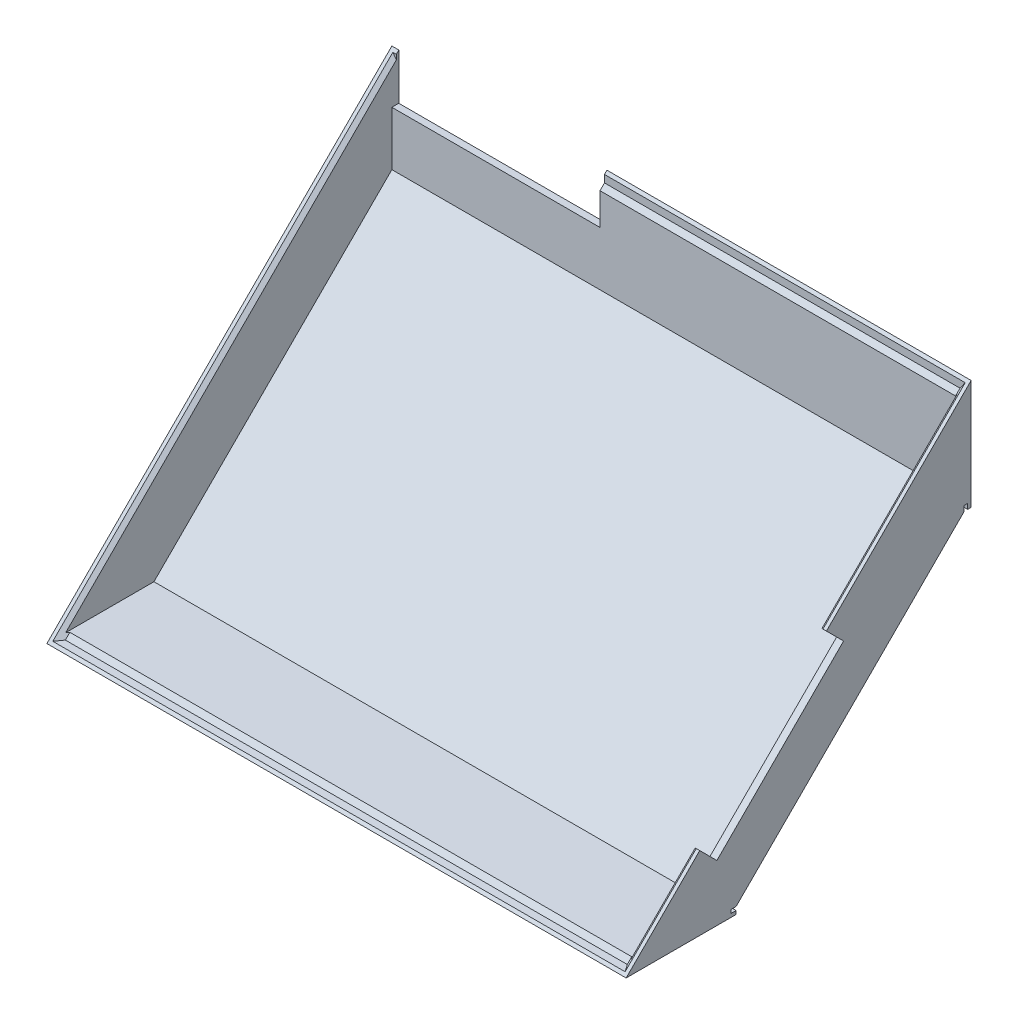
SolidWorks part; units mm, degrees
ref_plane "Front Plane" through (0, 0, 0) normal (0, 0, 1) x (1, 0, 0)
ref_plane "Top Plane" through (0, 0, 0) normal (0, 1, 0) x (1, 0, 0)
ref_plane "Right Plane" through (0, 0, 0) normal (1, 0, 0) x (0, 0, -1)
sketch "Sketch1" plane through (0, 0, 0) normal (1, 0, 0) x (0, 0, -1)
  line L0 (0, 0) -> (31.6985, 0)
  line L1 (99.4594, 67.7609) -> (99.4594, 99.4594)
  line L2 (99.4594, 99.4594) -> (0, 0)
  line L6 (31.6985, 2) -> (31.6985, 0)
  line L7 (97.4594, 67.7609) -> (99.4594, 67.7609)
  line L9 (97.4594, 67.7609) -> (31.6985, 2)
  dimension "D1" = 93
  dimension "D2" = 2
  dimension "D3" = 2
  dimension "D4" = 21
  dimension "D5" = 45
extrude "Boss-Extrude2" add sketch "Sketch1" along normal blind 167 contours L2 L0 L6 L9 L7 L1
sketch "Sketch5" plane through (167, 0, 0) normal (1, 0, 0) x (0, 0, -1)
  line L0 (99.4594, 99.4594) -> (0, 0) construction
  line L1 (97.4594, 97.4594) -> (2, 2)
  line L27 (29.6985, 2) -> (29.6985, 2.8284)
  line L28 (4.8284, 2) -> (29.6985, 2)
  line L29 (96.631, 69.7609) -> (97.4594, 69.7609)
  line L30 (29.6985, 2.8284) -> (96.631, 69.7609)
  line L31 (97.4594, 69.7609) -> (97.4594, 94.631)
  line L32 (97.4594, 94.631) -> (4.8284, 2)
  line L34 (2, 2) -> (28.8701, 2)
  line L36 (28.8701, 2) -> (97.4594, 70.5894)
  line L37 (97.4594, 70.5894) -> (97.4594, 97.4594)
  dimension "D1" = 2
extrude "Cut-Extrude2" cut sketch "Sketch5" against normal offset from surface (163 mm away) 2 from offset 2 up to face at (0, 39.4969, -59.9625) offset against normal yes
sketch "Sketch6" plane through (167, 0, 0) normal (1, 0, 0) x (0, 0, -1)
  line L0 (97.4594, 67.7609) -> (97.4594, 69.2609)
  line L1 (97.4594, 69.2609) -> (98.4594, 69.2609)
  line L2 (98.4594, 69.2609) -> (98.4594, 67.7609)
  line L3 (97.4594, 67.7609) -> (99.4594, 67.7609) construction
  line L4 (99.4594, 67.7609) -> (99.4594, 99.4594) construction
  line L5 (97.4594, 67.7609) -> (98.4594, 67.7609)
  line L6 (49.7297, 49.7297) -> (35405.0688, -35305.6094) construction
  line L7 (99.4594, 99.4594) -> (0, 0) construction
  line L8 (31.6985, 2) -> (31.6985, 1)
  line L9 (30.1985, 1) -> (31.6985, 1)
  line L10 (30.1985, 2) -> (30.1985, 1)
  line L11 (31.6985, 2) -> (30.1985, 2)
  point P13 (49.7297, 49.7297)
  dimension "D1" = 1
  dimension "D2" = 1.5
extrude "Base Slots" cut sketch "Sketch6" against normal through all
sketch "Sketch7" plane through (0, 0, 0) normal (0, 0.7071, 0.7071) x (1, 0, 0)
  line L4 (2, 118.8284) -> (165, 118.8284) construction
  line L5 (2, 21.8284) -> (165, 21.8284) construction
  line L8 (1, 139.6569) -> (1, 1)
  line L9 (1, 1) -> (166, 1)
  line L10 (166, 1) -> (166, 139.6569)
  line L11 (166, 139.6569) -> (1, 139.6569)
  line L12 (1, 139.6569) -> (1, 1)
  line L13 (1, 1) -> (166, 1)
  line L14 (166, 1) -> (166, 139.6569)
  line L15 (166, 139.6569) -> (1, 139.6569)
  dimension "D1" = 1
extrude "Cover slots" cut sketch "Sketch7" against normal blind 1.5 draft 45
sketch "Sketch8" plane through (167, 0, 0) normal (1, 0, 0) x (0, 0, -1)
  line L0 (26.163, 16.2635) -> (62.6899, 52.7904)
  line L1 (62.6899, 52.7904) -> (57.7401, 57.7401)
  line L2 (99.4594, 99.4594) -> (0, 0) construction
  line L3 (26.163, 16.2635) -> (21.2132, 21.2132)
  line L4 (21.2132, 21.2132) -> (57.7401, 57.7401)
  line L5 (97.4594, 67.7609) -> (31.6985, 2) construction
  dimension "D1" = 30
  dimension "D2" = 59
  dimension "D3" = 14
extrude "USB C Slots" cut sketch "Sketch8" against normal up to next
sketch "Sketch9" plane through (0, 0, -99.4594) normal (0, 0, -1) x (-1, 0, 0)
  line L0 (-62, 99.4594) -> (-62, 86.1609)
  line L1 (-167, 99.4594) -> (0, 99.4594) construction
  line L5 (-2, 99.4594) -> (-62, 99.4594)
  line L9 (-62, 86.1609) -> (-2, 86.1609)
  line L10 (-2, 86.1609) -> (-2, 99.4594)
  line L12 (0, 67.7609) -> (0, 99.4594) construction
  line L13 (-167, 67.7609) -> (0, 67.7609) construction
  dimension "D1" = 2
  dimension "D2" = 18.4
  dimension "D3" = 60
extrude "Screen Overhang" cut sketch "Sketch9" against normal up to next
